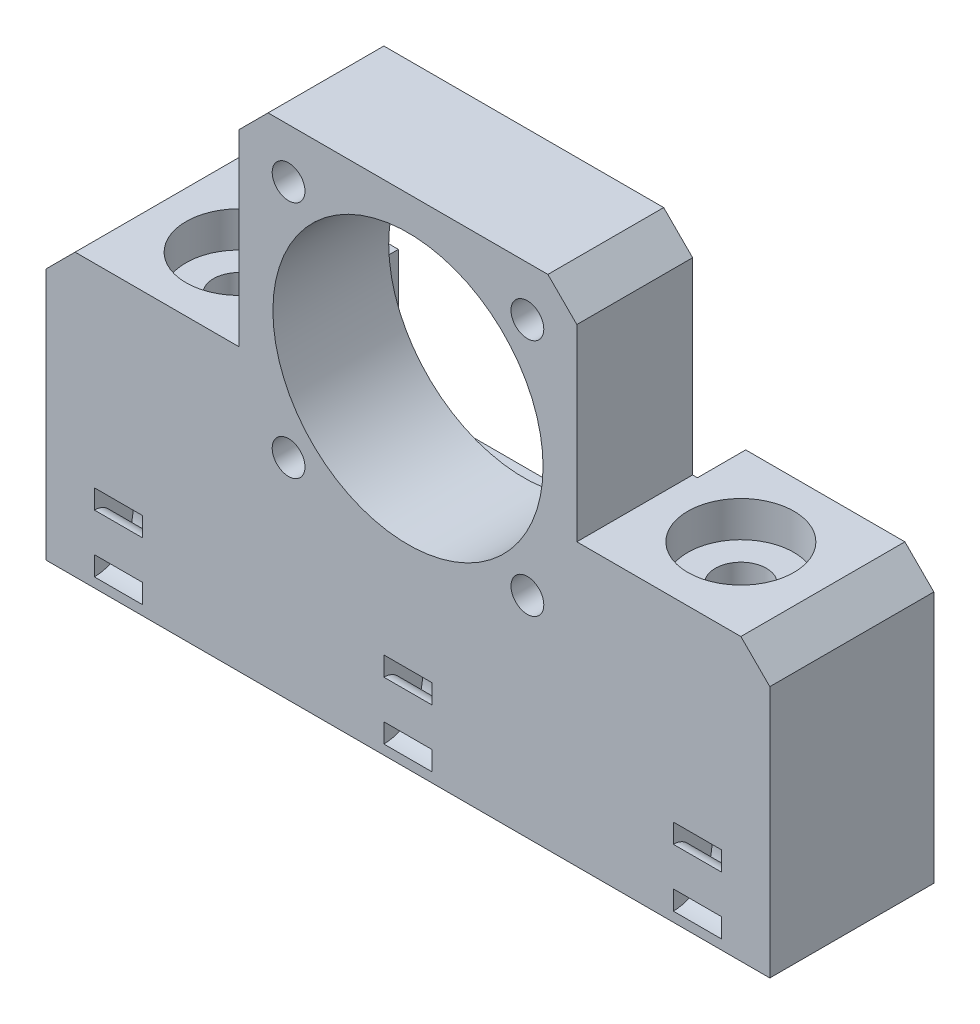
SolidWorks part; units mm, degrees
ref_plane "Plan de face" through (0, 0, 0) normal (0, 0, 1) x (1, 0, 0)
ref_plane "Plan de dessus" through (0, 0, 0) normal (0, 1, 0) x (1, 0, 0)
ref_plane "Plan de droite" through (0, 0, 0) normal (1, 0, 0) x (0, 0, -1)
sketch "Esquisse1" plane through (0, 0, 0) normal (0, 0, 1) x (1, 0, 0)
  line L4 (12.49, 17.5) -> (-12.49, 17.5)
  line L5 (-17.5, 12.49) -> (-17.5, -12.49)
  line L6 (-12.49, -17.5) -> (12.49, -17.5)
  line L7 (17.5, -12.49) -> (17.5, 12.49)
  line L8 (12.49, 17.5) -> (-12.49, 17.5)
  line L9 (-17.5, 12.49) -> (-17.5, -12.49)
  line L10 (-12.49, -17.5) -> (12.49, -17.5)
  line L11 (17.5, -12.49) -> (17.5, 12.49)
  circle A0 centre (0, 0) radius 14 construction
  circle A1 centre (-12.3744, -12.3744) radius 1.7 construction
  circle A2 centre (12.3744, -12.3744) radius 1.7 construction
  circle A3 centre (12.3744, 12.3744) radius 1.7 construction
  arc A4 (17.5, 12.49) -> (12.49, 17.5) centre (0, 0) ccw
  arc A5 (-12.49, 17.5) -> (-17.5, 12.49) centre (0, 0) ccw
  arc A6 (-17.5, -12.49) -> (-12.49, -17.5) centre (0, 0) ccw
  arc A7 (12.49, -17.5) -> (17.5, -12.49) centre (0, 0) ccw
  arc A8 (17.5, 12.49) -> (12.49, 17.5) centre (0, 0) ccw
  arc A9 (-12.49, 17.5) -> (-17.5, 12.49) centre (0, 0) ccw
  arc A10 (-17.5, -12.49) -> (-12.49, -17.5) centre (0, 0) ccw
  arc A11 (12.49, -17.5) -> (17.5, -12.49) centre (0, 0) ccw
  circle A12 centre (-12.3744, 12.3744) radius 1.7 construction
  circle A13 centre (0, 0) radius 14
  circle A14 centre (-12.3744, -12.3744) radius 1.7
  circle A15 centre (12.3744, -12.3744) radius 1.7
  circle A16 centre (12.3744, 12.3744) radius 1.7
  circle A17 centre (-12.3744, 12.3744) radius 1.7
  dimension "D1" = 0
extrude "Boss.-Extru.1" add sketch "Esquisse1" along normal blind 17
sketch "Esquisse2" plane through (0, 0, 17) normal (0, 0, 1) x (1, 0, 0)
  line L0 (-12.49, 17.5) -> (-14.5, 17.5)
  line L1 (-17.5, 14.5) -> (-17.5, -5)
  line L2 (-17.5, -5) -> (-34.5, -5)
  line L3 (-37.5, -8) -> (-37.5, -34.15)
  line L4 (-37.5, -34.15) -> (37.5, -34.15)
  line L5 (37.5, -34.15) -> (37.5, -8)
  line L6 (34.5, -5) -> (17.5, -5)
  line L7 (17.5, -5) -> (17.5, 14.5)
  line L8 (14.5, 17.5) -> (-12.49, 17.5)
  line L9 (-17.5, 12.49) -> (-17.5, -12.49) construction
  line L10 (17.5, -12.49) -> (17.5, 12.49) construction
  line L11 (-12.49, -17.5) -> (12.49, -17.5) construction
  line L12 (-34.5, -5) -> (-37.5, -8)
  line L13 (37.5, -8) -> (34.5, -5)
  line L14 (17.5, 14.5) -> (14.5, 17.5)
  line L15 (-14.5, 17.5) -> (-17.5, 14.5)
  circle A0 centre (12.3744, 12.3744) radius 1.7 construction
  circle A1 centre (12.3744, -12.3744) radius 1.7 construction
  circle A2 centre (-12.3744, -12.3744) radius 1.7 construction
  circle A3 centre (-12.3744, 12.3744) radius 1.7 construction
  circle A4 centre (0, 0) radius 14 construction
  circle A5 centre (12.3744, 12.3744) radius 1.7
  circle A6 centre (12.3744, -12.3744) radius 1.7
  circle A7 centre (-12.3744, -12.3744) radius 1.7
  circle A8 centre (-12.3744, 12.3744) radius 1.7
  circle A9 centre (0, 0) radius 14
  point P1 (-17.5, 17.5)
  point P4 (37.5, -5)
  point P5 (-37.5, -5)
  point P9 (17.5, 17.5)
  dimension "D1" = 16.65
  dimension "D2" = 29.15
  dimension "D3" = 29.15
  dimension "D4" = 20
  dimension "D5" = 20
extrude "Boss.-Extru.2" add sketch "Esquisse2" against normal blind 17
sketch "Esquisse3" plane through (0, -5, 0) normal (0, 1, 0) x (1, 0, 0)
  line L0 (26, 0) -> (26, -17) construction
  line L1 (34.5, 0) -> (17.5, 0) construction
  line L2 (34.5, -17) -> (17.5, -17) construction
  line L3 (-26, 0) -> (-26, -17) construction
  line L4 (-17.5, 0) -> (-34.5, 0) construction
  line L5 (-17.5, -17) -> (-34.5, -17) construction
hole_wizard "Chambrage pour vis à tête ronde bombée M51" positions "Esquisse4" profile "Esquisse5" counterbore size "M5" standard "Ansi Metric"
sketch "Esquisse4" plane through (0, -5, 0) normal (0, 1, 0) x (1, 0, 0)
  line L0 (-26, 0) -> (-26, -17) construction
  line L1 (26, 0) -> (26, -17) construction
  point P0 (-26, -8.5)
  point P2 (26, -8.5)
sketch "Esquisse5" plane through (-26, -5, 8.5) normal (1, 0, 0) x (0, 0, 1)
  line L0 (0, 0) -> (0, 36.5923)
  line L1 (0, 36.5923) -> (2.65, 35)
  line L2 (2.65, 35) -> (2.65, 3.7)
  line L3 (2.65, 3.7) -> (5.5, 3.7)
  line L4 (5.5, 3.7) -> (5.5, 0)
  line L5 (5.5, 0) -> (0, 0)
  line L10 (0, 36.5923) -> (-2.65, 35) construction
  line L11 (0, -6.35) -> (0, 107.95) construction
  dimension "Diamètre du perçage" = 5.3
  dimension "Profondeur du perçage" = 35
  dimension "Diamètre du chambrage" = 11
  dimension "Profondeur du chambrage" = 3.7
  dimension "Angle de pointe" = 118
sketch "Esquisse7" plane through (0, 0, 17) normal (0, 0, 1) x (1, 0, 0)
  line L0 (-37.5, -29.15) -> (37.5, -29.15) construction
  line L1 (-37.5, -8) -> (-37.5, -34.15) construction
  line L2 (37.5, -34.15) -> (37.5, -8) construction
  line L3 (-37.5, -34.15) -> (37.5, -34.15) construction
  line L4 (2.5, -25.15) -> (2.5, -27.15)
  line L5 (-32.5, -25.15) -> (-27.5, -25.15)
  line L6 (-32.5, -25.15) -> (-32.5, -27.15)
  line L7 (-32.5, -27.15) -> (-27.5, -27.15)
  line L8 (-27.5, -25.15) -> (-27.5, -27.15)
  line L9 (-2.5, -25.15) -> (2.5, -25.15)
  line L10 (-2.5, -27.15) -> (2.5, -27.15)
  line L11 (-2.5, -25.15) -> (-2.5, -27.15)
  line L12 (32.5, -25.15) -> (32.5, -27.15)
  line L13 (27.5, -25.15) -> (32.5, -25.15)
  line L14 (27.5, -27.15) -> (32.5, -27.15)
  line L15 (27.5, -25.15) -> (27.5, -27.15)
  dimension "D1" = 5
  dimension "D2" = 2
  dimension "D3" = 2
  dimension "D4" = 5
  dimension "D5" = 5
  dimension "D7" = 25
  dimension "D6" = 3
revolve "Enlèvement de matière-Révolution1" cut sketch "Esquisse7" angle 360 about L0
sketch "Esquisse8" plane through (0, 0, 0) normal (0, 0, -1) x (-1, 0, 0)
  line L0 (-12.49, 17.5) -> (-14.5, 17.5)
  line L1 (-14.5, 17.5) -> (-17.5, 14.5)
  line L2 (-17.5, 14.5) -> (-17.5, 12.49)
  line L3 (12.49, 17.5) -> (14.5, 17.5)
  line L4 (-12.49, -17.5) -> (12.49, -17.5)
  line L5 (17.5, -12.49) -> (17.5, 12.49)
  line L6 (12.49, 17.5) -> (-12.49, 17.5)
  line L7 (-17.5, 12.49) -> (-17.5, -12.49)
  line L8 (-12.49, -17.5) -> (12.49, -17.5)
  line L9 (17.5, -12.49) -> (17.5, 12.49)
  line L10 (12.49, 17.5) -> (-12.49, 17.5)
  line L11 (-17.5, 12.49) -> (-17.5, -12.49)
  line L12 (14.5, 17.5) -> (17.5, 14.5)
  line L13 (17.5, 14.5) -> (17.5, 12.49)
  arc A14 (-17.5, -12.49) -> (-12.49, -17.5) centre (0, 0) ccw
  arc A15 (12.49, -17.5) -> (17.5, -12.49) centre (0, 0) ccw
  arc A16 (17.5, 12.49) -> (12.49, 17.5) centre (0, 0) ccw
  arc A17 (-12.49, 17.5) -> (-17.5, 12.49) centre (0, 0) ccw
  arc A18 (-17.5, -12.49) -> (-12.49, -17.5) centre (0, 0) ccw
  arc A19 (12.49, -17.5) -> (17.5, -12.49) centre (0, 0) ccw
  dimension "D6" = 0
extrude "Enlèv. mat.-Extru.1" cut sketch "Esquisse8" against normal blind 5
sketch "Esquisse9" plane through (0, 0, 0) normal (0, 0, -1) x (-1, 0, 0)
  line L0 (17.5, -12.49) -> (17.5, -5) construction
  line L1 (-12.49, -17.5) -> (12.49, -17.5) construction
  line L2 (-17.5, -5) -> (-17.5, -12.49) construction
  line L3 (17.5, -12.49) -> (17.5, -5)
  line L4 (-12.49, -17.5) -> (12.49, -17.5)
  line L5 (-17.5, -5) -> (-17.5, -12.49)
  line L6 (-17.5, -5) -> (17.5, -5)
  line L7 (-18, -4.5) -> (-18, -12.6491)
  line L8 (-12.6491, -18) -> (12.6491, -18)
  line L9 (18, -12.6491) -> (18, -4.5)
  line L10 (-18, -4.5) -> (18, -4.5)
  arc A0 (12.49, -17.5) -> (17.5, -12.49) centre (0, 0) ccw construction
  arc A1 (-17.5, -12.49) -> (-12.49, -17.5) centre (0, 0) ccw construction
  arc A2 (12.49, -17.5) -> (17.5, -12.49) centre (0, 0) ccw
  arc A3 (-17.5, -12.49) -> (-12.49, -17.5) centre (0, 0) ccw
  arc A4 (-18, -12.6491) -> (-12.6491, -18) centre (0, 0) ccw
  arc A5 (12.6491, -18) -> (18, -12.6491) centre (0, 0) ccw
  dimension "D1" = 0.5
extrude "Enlèv. mat.-Extru.2" cut sketch "Esquisse9" against normal up to surface (5 mm away) up to face at (-14, 0, 5)
